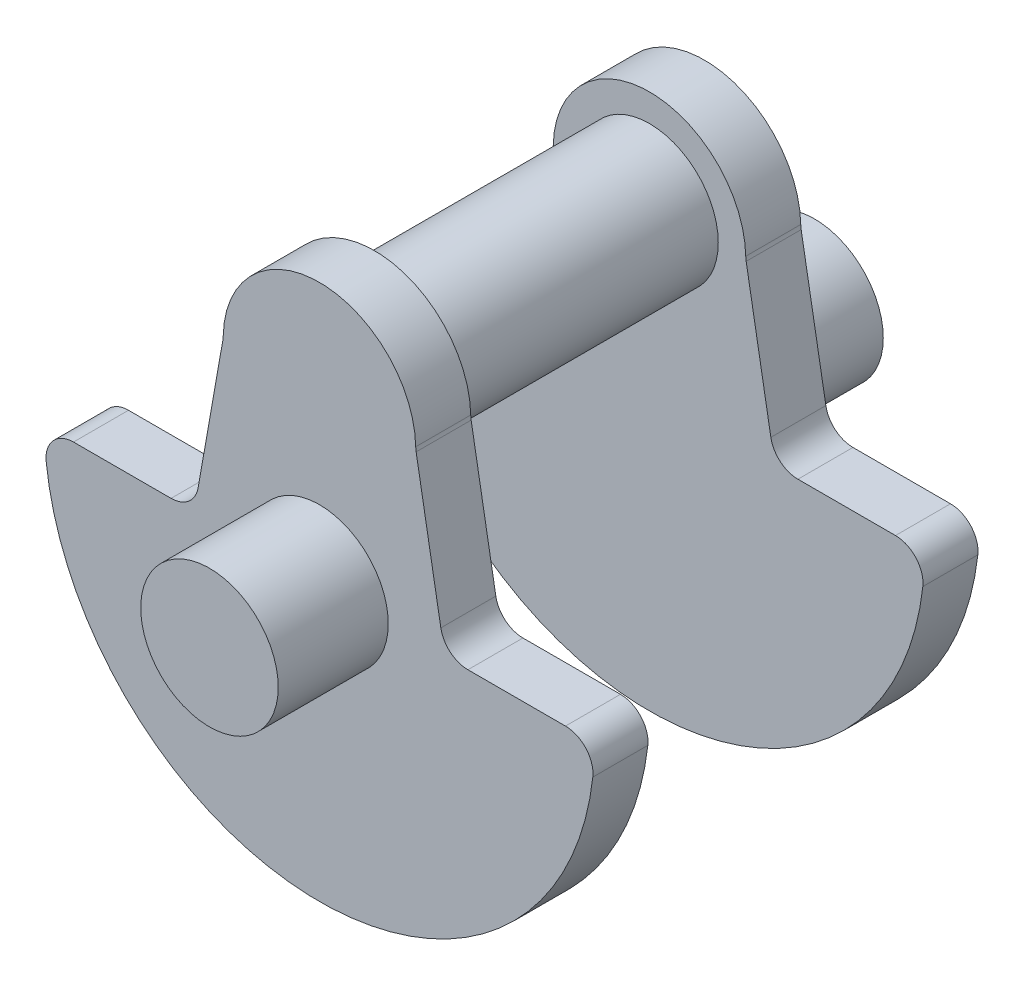
SolidWorks part; units mm, degrees
ref_plane "Front Plane" through (0, 0, 0) normal (0, 0, 1) x (1, 0, 0)
ref_plane "Top Plane" through (0, 0, 0) normal (0, 1, 0) x (1, 0, 0)
ref_plane "Right Plane" through (0, 0, 0) normal (1, 0, 0) x (0, 0, -1)
sketch "Sketch1" plane through (0, 0, 0) normal (0, 0, 1) x (1, 0, 0)
  line L0 (-17.5, 30) -> (-22.7898, 0)
  line L1 (-22.7898, 0) -> (-50, 0)
  line L2 (17.5, 30) -> (22.7898, 0)
  line L3 (22.7898, 0) -> (50, 0)
  line L4 (0, 30) -> (0, 0)
  arc A0 (17.5, 30) -> (-17.5, 30) centre (0, 30) ccw
  arc A1 (50, 0) -> (-50, 0) centre (0, 0) cw
  dimension "D1" = 50
  dimension "D2" = 35
  dimension "D3" = 30
extrude "Boss-Extrude1" add sketch "Sketch1" against normal blind 10
fillet "Fillet1" radius 5 6 edges at (50, 0, -5) (22.7898, 0, -5) (17.5, 30, -5) (-17.5, 30, -5) (-22.7898, 0, -5) (-50, 0, -5)
sketch "Sketch2" plane through (0, 0, 0) normal (0, 0, 1) x (1, 0, 0)
  circle A0 centre (0, 0) radius 12.5
extrude "Boss-Extrude2" add sketch "Sketch2" along normal blind 20
sketch "Sketch3" plane through (0, 0, -10) normal (0, 0, -1) x (-1, 0, 0)
  circle A0 centre (0, 30) radius 12.5
extrude "Boss-Extrude3" add sketch "Sketch3" along normal blind 50
ref_plane "Plane1" through (0, 0, -35) normal (0, 0, -1) x (-1, 0, 0)
mirror "Mirror1" about plane through (0, 0, -35) normal (0, 0, -1) of "Fillet1", "Boss-Extrude2", "Boss-Extrude1"
